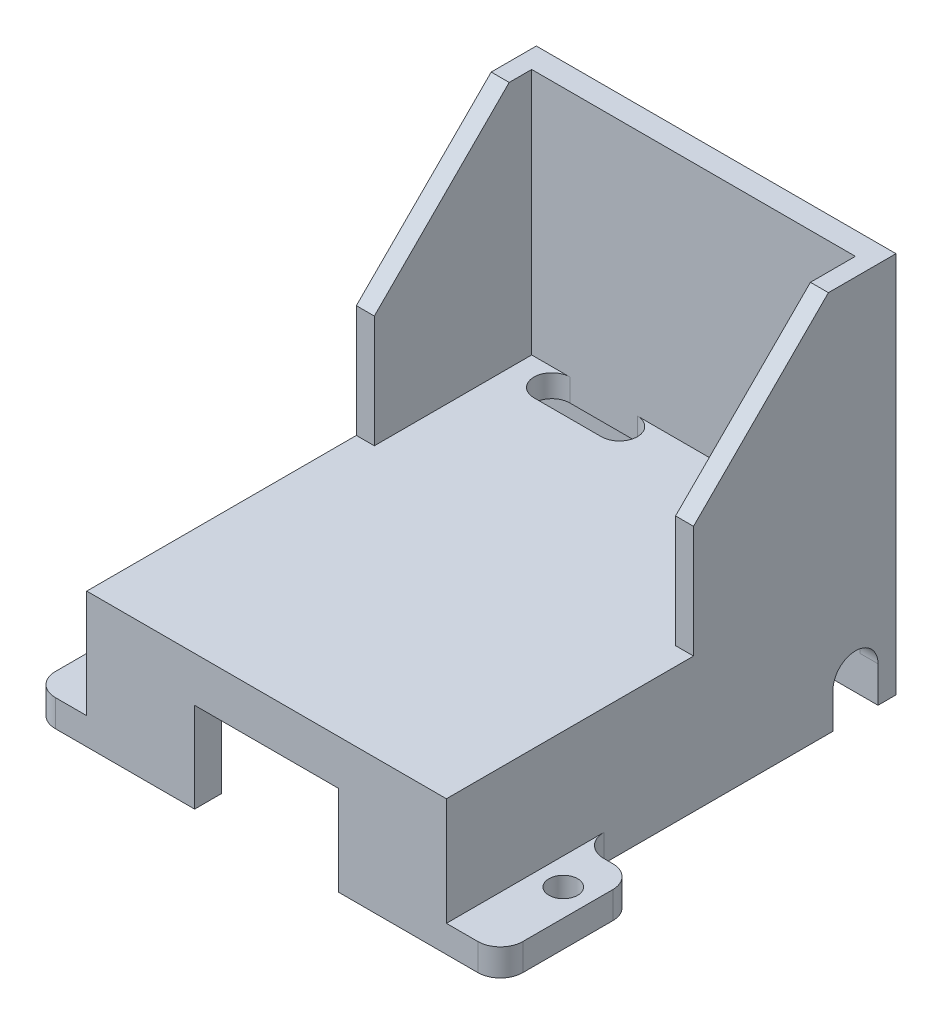
SolidWorks part; units mm, degrees
ref_plane "Front Plane" through (0, 0, 0) normal (0, 0, 1) x (1, 0, 0)
ref_plane "Top Plane" through (0, 0, 0) normal (0, 1, 0) x (1, 0, 0)
ref_plane "Right Plane" through (0, 0, 0) normal (1, 0, 0) x (0, 0, -1)
sketch "Sketch1" plane through (0, 0, 0) normal (0, 1, 0) x (1, 0, 0)
  line L1 (0, 0) -> (40, 0)
  line L2 (0, 0) -> (0, 50)
  line L3 (0, 50) -> (40, 50)
  line L4 (40, 0) -> (40, 50)
  dimension "D1" = 50
  dimension "D2" = 40
extrude "Boss-Extrude1" add sketch "Sketch1" along normal blind 15
sketch "Sketch2" plane through (0, 0, 0) normal (0, -1, 0) x (1, 0, 0)
  line L0 (0, 0) -> (40, 0) construction
  line L1 (12, 0) -> (28, 0)
  line L2 (12, 0) -> (12, -3)
  line L3 (12, -3) -> (28, -3)
  line L4 (28, 0) -> (28, -3)
  line L5 (40, -50) -> (0, -50) construction
  point P6 (20, -3)
  point P7 (20, -50)
  point P8 (0, 0)
  dimension "D1" = 16
  dimension "D2" = 3
extrude "Cut-Extrude1" cut sketch "Sketch2" against normal blind 10
sketch "Sketch3" plane through (0, 0, 0) normal (0, -1, 0) x (1, 0, 0)
  line L0 (12, -3) -> (28, -3) construction
  line L1 (2, -3) -> (38, -3)
  line L2 (2, -3) -> (2, -48)
  line L3 (2, -48) -> (38, -48)
  line L4 (38, -3) -> (38, -48)
  line L5 (0, -50) -> (0, 0) construction
  line L6 (40, 0) -> (40, -50) construction
  line L7 (40, -50) -> (0, -50) construction
  dimension "D1" = 2
  dimension "D2" = 2
  dimension "D3" = 2
extrude "Cut-Extrude2" cut sketch "Sketch3" against normal offset from surface (12.5 mm away) 2.5 up to face at (20, 15, -25)
sketch "Sketch4" plane through (0, 15, 0) normal (0, 1, 0) x (1, 0, 0)
  line L0 (40, 0) -> (40, 50) construction
  line L1 (0, 50) -> (40, 50)
  line L2 (0, 50) -> (0, 47.4843)
  line L3 (0, 47.4843) -> (40, 47.4843)
  line L4 (40, 50) -> (40, 47.4843)
extrude "Boss-Extrude2" add sketch "Sketch4" along normal blind 27.5
sketch "Sketch5" plane through (0, 15, 0) normal (0, 1, 0) x (1, 0, 0)
  line L0 (6.25, 45.4843) -> (13.75, 45.4843) construction
  line L1 (6.25, 47.4843) -> (13.75, 47.4843)
  line L2 (6.25, 43.4843) -> (13.75, 43.4843)
  line L3 (0, 47.4843) -> (40, 47.4843) construction
  line L4 (25.75, 45.4843) -> (33.25, 45.4843) construction
  line L5 (25.75, 47.4843) -> (33.25, 47.4843)
  line L6 (25.75, 43.4843) -> (33.25, 43.4843)
  line L8 (0, 0) -> (20, 0)
  line L9 (0, 0) -> (40, 0) construction
  line L11 (40, 0) -> (40, 47.4843) construction
  arc A0 (6.25, 47.4843) -> (6.25, 43.4843) centre (6.25, 45.4843) ccw
  arc A1 (13.75, 43.4843) -> (13.75, 47.4843) centre (13.75, 45.4843) ccw
  arc A2 (25.75, 47.4843) -> (25.75, 43.4843) centre (25.75, 45.4843) ccw
  arc A3 (33.25, 43.4843) -> (33.25, 47.4843) centre (33.25, 45.4843) ccw
  point P2 (10, 45.4843)
  point P11 (29.5, 45.4843)
  point P23 (10, 0)
  point P24 (0, 0)
  line M9 (40, 47.4843) -> (0, 47.4843)
  dimension "D1" = 4
  dimension "D2" = 7.5
  dimension "D3" = 7.5
  dimension "D4" = 10.5
extrude "Cut-Extrude3" cut sketch "Sketch5" against normal through all contours L2 A1 A0 M9 | L6 A3 A2 M9
sketch "Sketch6" plane through (0, 15, 0) normal (0, 1, 0) x (1, 0, 0)
  line L5 (0, 0) -> (40, 0) construction
  line L7 (0, 47.4843) -> (2, 47.4843)
  line L8 (0, 47.4843) -> (0, 29.9843)
  line L9 (0, 29.9843) -> (2, 29.9843)
  line L10 (2, 47.4843) -> (2, 29.9843)
  line L11 (40, 47.4843) -> (38, 47.4843)
  line L12 (40, 47.4843) -> (40, 27.4843)
  line L13 (40, 27.4843) -> (38, 27.4843)
  line L14 (38, 47.4843) -> (38, 27.4843)
  point P6 (20, 0)
  dimension "D2" = 17.5
extrude "Boss-Extrude3" add sketch "Sketch6" along normal blind 27.5
sketch "Sketch7" plane through (0, 0, 0) normal (-1, 0, 0) x (0, 0, 1)
  line L0 (-48, 0) -> (-48, 4)
  line L1 (-48, 12.5) -> (-48, 0) construction
  line L2 (-43, 4) -> (-43, 0)
  line L3 (-50, 0) -> (0, 0) construction
  arc A0 (-48, 4) -> (-43, 4) centre (-45.5, 4) cw
  point P10 (-43, 4.0849)
  line M7 (-50, 0) -> (0, 0)
  dimension "D1" = 5
  dimension "D2" = 4
extrude "Cut-Extrude5" cut sketch "Sketch7" against normal through all and the other way through all contours A0 L0 L2 M7
sketch "Sketch8" plane through (40, 0, 0) normal (1, 0, 0) x (0, 0, -1)
  line L1 (0, 0) -> (15, 0)
  line L2 (0, 0) -> (0, 3)
  line L3 (0, 3) -> (15, 3)
  line L4 (15, 0) -> (15, 3)
  dimension "D1" = 3
  dimension "D2" = 15
extrude "Boss-Extrude4" add sketch "Sketch8" along normal blind 6
sketch "Sketch9" plane through (0, 3, 0) normal (0, 1, 0) x (1, 0, 0)
  line L0 (46, 0) -> (40, 0) construction
  circle A0 centre (43, 10) radius 1.6
  point P4 (43, 0)
  point P5 (0, 0)
  dimension "D1" = 3.2
  dimension "D2" = 10
extrude "Cut-Extrude6" cut sketch "Sketch9" against normal through all
ref_plane "Plane1" through (20, 0, 0) normal (-1, 0, 0) x (0, 0, 1)
mirror "Mirror1" about plane through (20, 0, 0) normal (-1, 0, 0) of "Cut-Extrude6", "Boss-Extrude4"
fillet "Fillet1" radius 2.5 6 edges at (0, 1.5, -15) (40, 1.5, -15) (46, 1.5, -15) (-6, 1.5, -15) (46, 1.5, 0) (-6, 1.5, 0)
chamfer "Chamfer3" distance 15 angle 45 2 edges at (1, 42.5, -29.9843) (39, 42.5, -27.4843)
